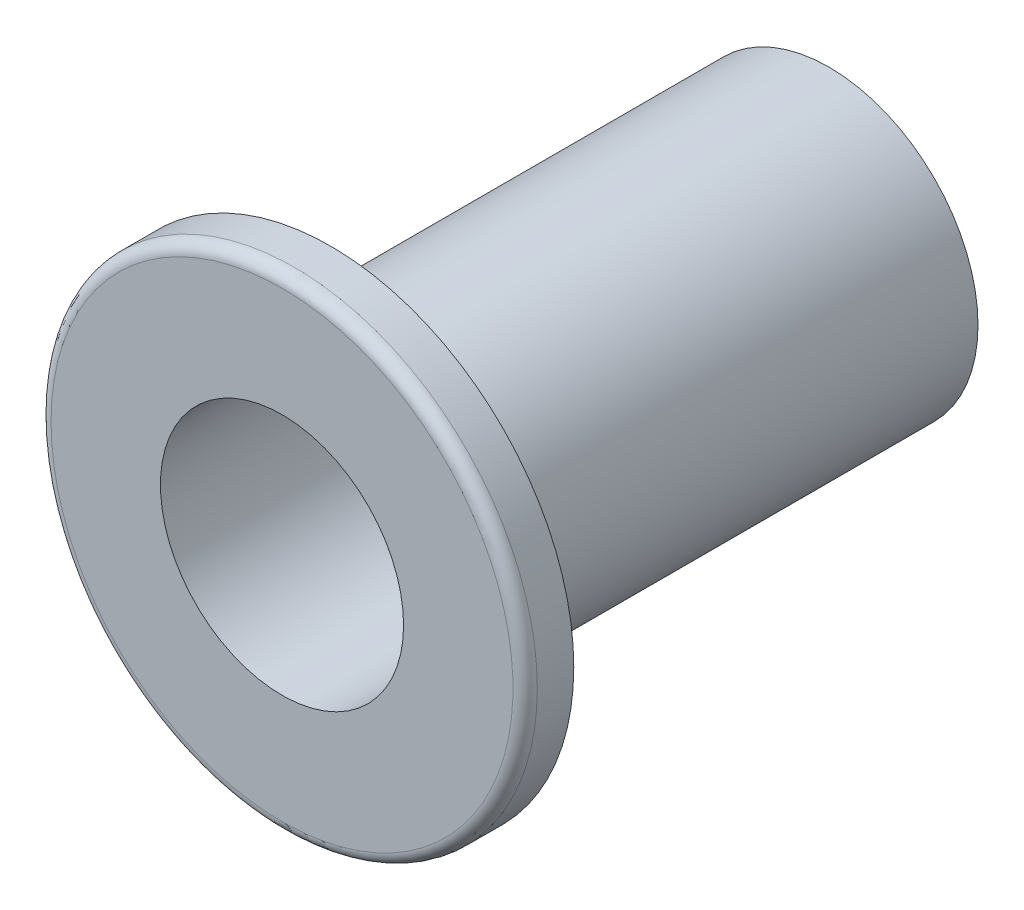
SolidWorks part; units mm, degrees
material "AISI 304"
ref_plane "前视基准面" through (0, 0, 0) normal (0, 0, 1) x (1, 0, 0)
ref_plane "上视基准面" through (0, 0, 0) normal (0, 1, 0) x (1, 0, 0)
ref_plane "右视基准面" through (0, 0, 0) normal (1, 0, 0) x (0, 0, -1)
sketch "草图1" plane through (0, 0, 0) normal (1, 0, 0) x (0, 0, -1)
  line L0 (0, 0) -> (6.0548, 0) construction
  line L1 (0, 2.45) -> (0, 4)
  line L2 (0, 4) -> (-0.8, 4)
  line L3 (-0.8, 4) -> (-0.8, 2)
  line L5 (8.2, 1.5) -> (8.2, 2.45)
  line L6 (8.2, 2.45) -> (0, 2.45)
  line L9 (3.7, 1.5) -> (8.2, 1.5)
  line L10 (3.7, 1.5) -> (3.7, 2)
  line L11 (3.7, 2) -> (-0.8, 2)
  dimension "D1" = 8
  dimension "D2" = 4.9
  dimension "D3" = 3
  dimension "D4" = 4.5
  dimension "D5" = 0.8
  dimension "D6" = 9
  dimension "D7" = 4
revolve "旋转1" add sketch "草图1" angle 360 about L0
fillet "圆角1" radius 0.2 1 edges at (4, 0, 0.8)
